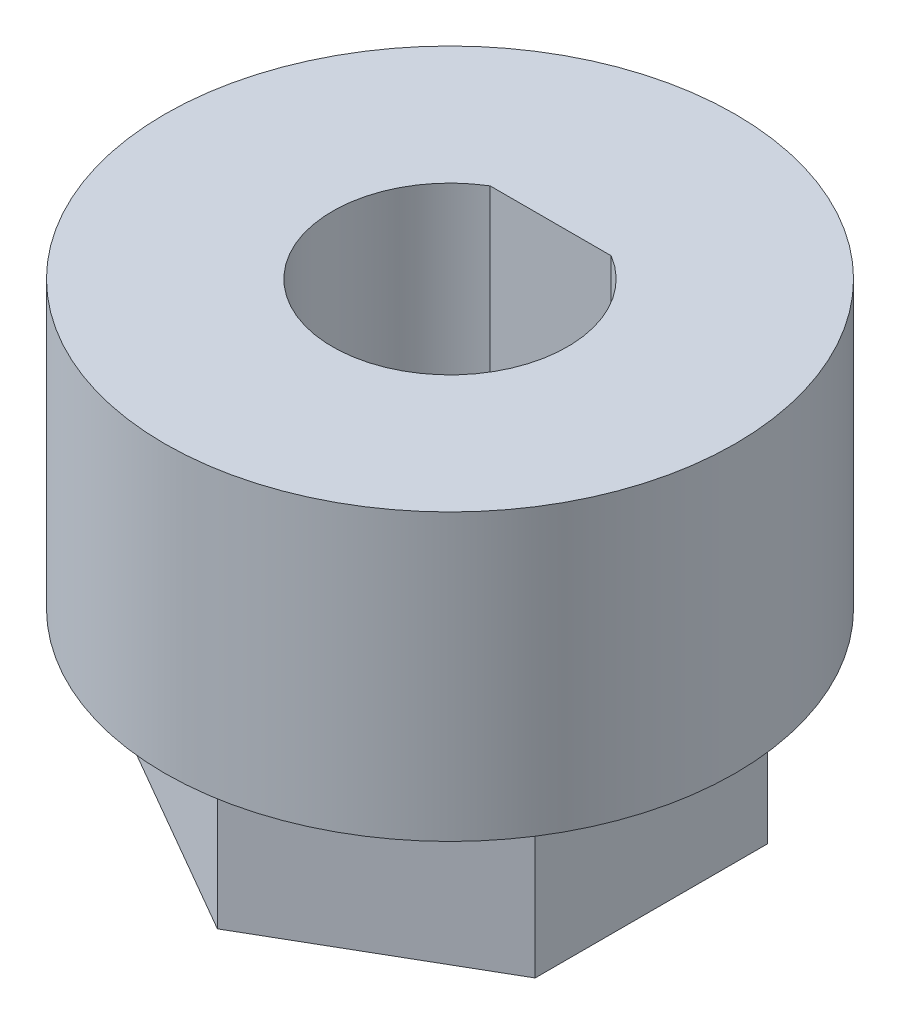
SolidWorks part; units mm, degrees
ref_plane "Front Plane" through (0, 0, 0) normal (0, 0, 1) x (1, 0, 0)
ref_plane "Top Plane" through (0, 0, 0) normal (0, 1, 0) x (1, 0, 0)
ref_plane "Right Plane" through (0, 0, 0) normal (1, 0, 0) x (0, 0, -1)
sketch "Sketch1" plane through (0, 0, 0) normal (0, 1, 0) x (1, 0, 0)
  line L0 (0, 6.9282) -> (0, -6.9282) construction
  line L1 (-6, -3.4641) -> (6, 3.4641) construction
  line L2 (6, -3.4641) -> (-6, 3.4641) construction
  line L3 (-6, 3.4641) -> (0, 6.9282)
  line L4 (0, 6.9282) -> (6, 3.4641)
  line L5 (6, 3.4641) -> (6, -3.4641)
  line L6 (6, -3.4641) -> (0, -6.9282)
  line L7 (0, -6.9282) -> (-6, -3.4641)
  line L8 (-6, -3.4641) -> (-6, 3.4641)
  dimension "D1" = 60
  dimension "D2" = 60
  dimension "D3" = 12
extrude "Boss-Extrude1" add sketch "Sketch1" along normal blind 4.8
sketch "Sketch2" plane through (0, 4.8, 0) normal (0, 1, 0) x (1, 0, 0)
  circle A0 centre (0, 0) radius 8.5
  dimension "D1" = 17
extrude "Boss-Extrude2" add sketch "Sketch2" along normal blind 8.5
sketch "Sketch3" plane through (0, 13.3, 0) normal (0, 1, 0) x (1, 0, 0)
  line L0 (-1.6583, 2.5) -> (1.6583, 2.5) construction
  line L1 (-3.5908, -3) -> (3.9178, -3) construction
  line L2 (-1.8028, 3) -> (1.8028, 3)
  arc A0 (-1.6583, 2.5) -> (1.6583, 2.5) centre (0, 0) ccw construction
  arc A1 (-1.8028, 3) -> (1.8028, 3) centre (0, 0) ccw
  dimension "D1" = 3
  dimension "D2" = 5.5
  dimension "D3" = 0.5
extrude "Cut-Extrude1" cut sketch "Sketch3" against normal through all
